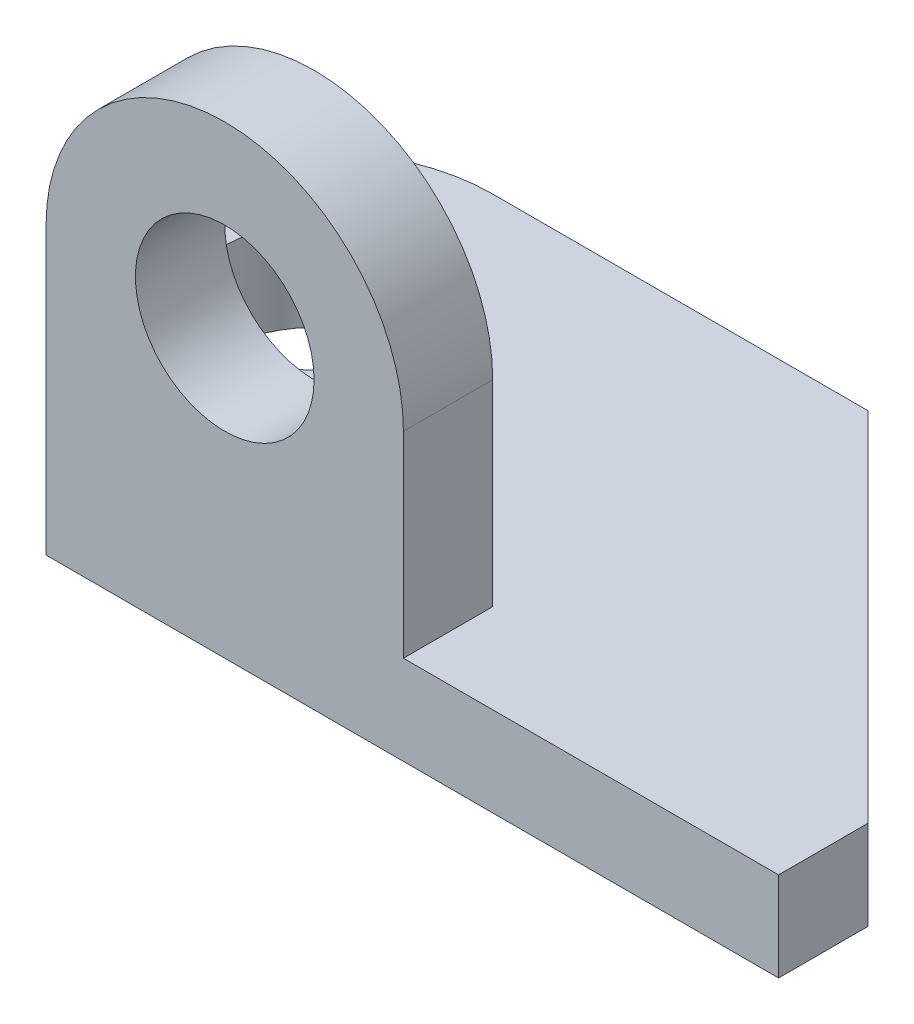
SolidWorks part; units mm, degrees
ref_plane "Front Plane" through (0, 0, 0) normal (0, 0, 1) x (1, 0, 0)
ref_plane "Top Plane" through (0, 0, 0) normal (0, 1, 0) x (1, 0, 0)
ref_plane "Right Plane" through (0, 0, 0) normal (1, 0, 0) x (0, 0, -1)
sketch "Sketch1" plane through (0, 0, 0) normal (0, 1, 0) x (1, 0, 0)
  line L0 (0, 0) -> (1016, 0)
  line L1 (1016, 0) -> (1016, 254)
  line L2 (1016, 254) -> (0, 254)
  line L3 (0, 254) -> (0, 0)
  line L4 (1016, 0) -> (2082.8, 0)
  line L5 (2082.8, 0) -> (2082.8, 254)
  line L6 (2082.8, 254) -> (1066.8, 1270)
  line L7 (1066.8, 1270) -> (0, 1270)
  arc A0 (0, 1270) -> (0, 254) centre (0, 762) ccw
  circle A1 centre (0, 762) radius 254
  dimension "D5" = 508
  dimension "D6" = 508
  dimension "D1" = 1016
  dimension "D2" = 254
  dimension "D3" = 1066.8
  dimension "D4" = 1066.8
extrude "Boss-Extrude1" add sketch "Sketch1" along normal blind 254 contours L7 A0 L2 L1 L4 L5 L6 A1 | L2 L3 L0 L1
sketch "Sketch3" plane through (0, 0, 0) normal (0, 0, 1) x (1, 0, 0)
  line L0 (0, 254) -> (0, 812.8)
  line L1 (1016, 812.8) -> (1016, 254)
  line L2 (0, 254) -> (2082.8, 254) construction
  arc A0 (0, 812.8) -> (1016, 812.8) centre (508, 812.8) cw
  circle A1 centre (508, 812.8) radius 254
  point P10 (508, 1320.8)
  line M3 (2082.8, 254) -> (0, 254)
  dimension "D1" = 508
  dimension "D2" = 508
  dimension "D3" = 1066.8
extrude "Boss-Extrude3" add sketch "Sketch3" against normal blind 254 contours A0 L0 L1 A1 M3
